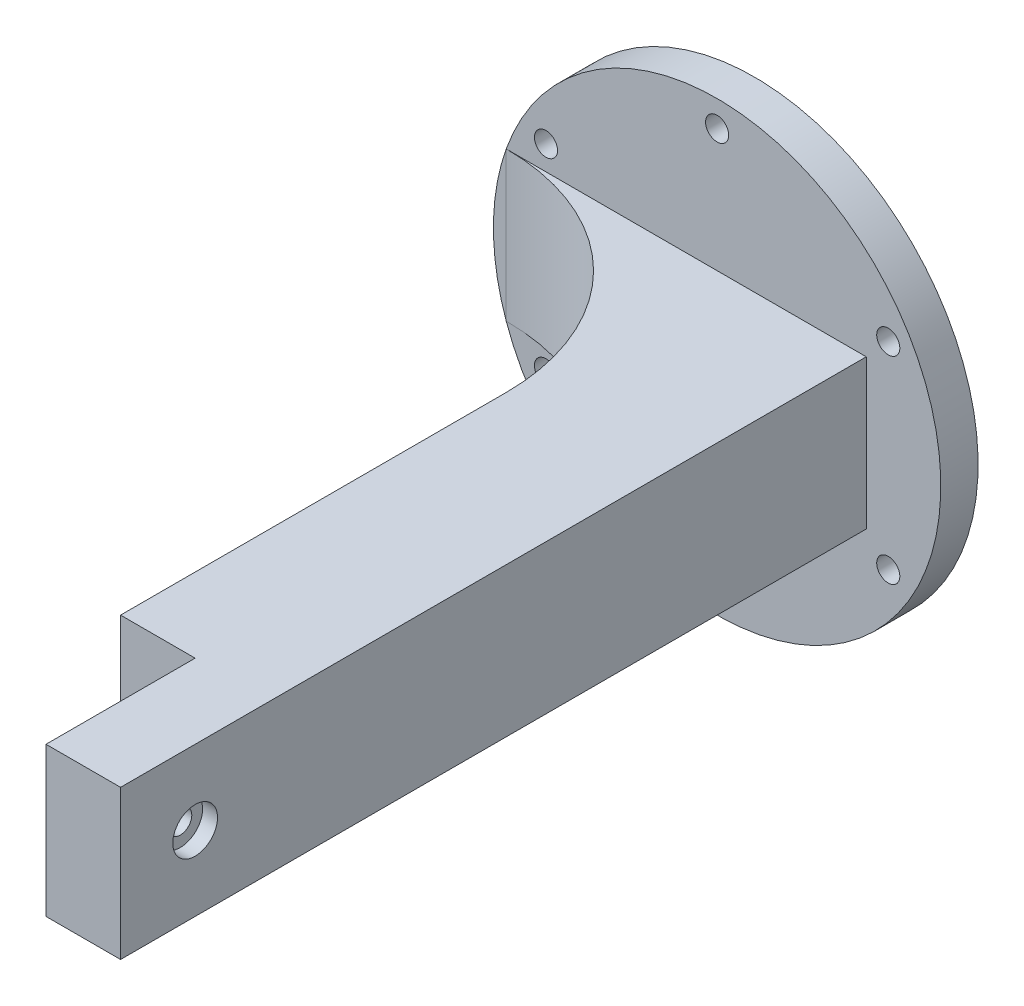
SolidWorks part; units mm, degrees
ref_plane "前视基准面" through (0, 0, 0) normal (0, 0, 1) x (1, 0, 0)
ref_plane "上视基准面" through (0, 0, 0) normal (0, 1, 0) x (1, 0, 0)
ref_plane "右视基准面" through (0, 0, 0) normal (1, 0, 0) x (0, 0, -1)
other "Configuration Table"
sketch "草图1" plane through (0, 0, 0) normal (0, 0, 1) x (1, 0, 0)
  line L1 (-16.3775, 3.1798) -> (3.6225, 3.1798)
  line L2 (-16.3775, 3.1798) -> (-16.3775, -16.8202)
  line L3 (-16.3775, -16.8202) -> (3.6225, -16.8202)
  line L4 (3.6225, 3.1798) -> (3.6225, -16.8202)
extrude "凸台-拉伸1" add sketch "草图1" along normal blind 140 contours L2 L1 L4 L3
sketch "草图2" plane through (0, 0, 0) normal (0, 0, -1) x (-1, 0, 0)
  line L1 (16.3775, 3.1798) -> (16.3775, -16.8202) construction
  circle A0 centre (16.3775, -6.8202) radius 30
  circle A4 centre (-6.5721, 6.4298) radius 1.55
  circle A5 centre (16.3775, 19.6798) radius 1.55
  circle A6 centre (39.3272, 6.4298) radius 1.55
  circle A7 centre (39.3272, -20.0702) radius 1.55
  circle A8 centre (16.3775, -33.3202) radius 1.55
  circle A9 centre (-6.5721, -20.0702) radius 1.55
extrude "凸台-拉伸2" add sketch "草图2" along normal blind 5 contours A4 | A9 | A8 | A7 | A0 | A6 | A5
sketch "草图3" plane through (0, 0, 0) normal (0, 0, 1) x (1, 0, 0)
  line L0 (-16.3775, 3.1798) -> (-44.6618, 3.1798)
  line L1 (-44.6618, 3.1798) -> (-44.6618, -16.8202)
  line L2 (-44.6618, -16.8202) -> (-16.3775, -16.8202)
  line L3 (-16.3775, 3.1798) -> (-16.3775, -16.8202)
  circle A0 centre (-16.3775, -6.8202) radius 30 construction
extrude "凸台-拉伸3" add sketch "草图3" along normal blind 28.2843 contours L3 L2 L1 L0
sketch "草图4" plane through (0, 3.1798, 0) normal (0, 1, 0) x (1, 0, 0)
  line L0 (-44.6618, -28.2843) -> (-44.6618, 0) construction
  line L1 (-44.6618, 0) -> (-44.6618, -28.2843)
  line L2 (-44.6618, -28.2843) -> (-16.3775, -28.2843)
  arc A0 (-16.3775, -28.2843) -> (-44.6618, 0) centre (-44.6618, -28.2843) ccw
extrude "切除-拉伸1" cut sketch "草图4" against normal blind 28.2843 contours L2 A0 L1
sketch "草图6" plane through (0, 3.1798, 0) normal (0, 1, 0) x (1, 0, 0)
  line L0 (3.6225, -140) -> (3.6225, -100)
  line L1 (3.6225, -140) -> (3.6225, 0) construction
  line L3 (-16.3775, -140) -> (-16.3775, -28.2843) construction
  line L4 (-16.3775, -100) -> (-16.3775, -140)
  line L5 (-16.3775, -140) -> (3.6225, -140)
  line L6 (-6.3775, -100) -> (-6.3775, -80)
  line L7 (-6.3775, -80) -> (-16.3775, -80)
  line L8 (-16.3775, -80) -> (-16.3775, -100)
  line L9 (-6.3775, -100) -> (3.6225, -100)
extrude "切除-拉伸2" cut sketch "草图6" against normal blind 28.2843 contours L9 L0 L5 L4 L8 L7 L6
sketch "草图7" plane through (-6.3775, 0, 0) normal (-1, 0, 0) x (0, 0, 1)
  line L0 (80, 3.1798) -> (100, -16.8202)
  line L1 (100, -16.8202) -> (100, 3.1798) construction
  circle A0 centre (90, -6.8202) radius 1.55
extrude "切除-拉伸3" cut sketch "草图7" against normal blind 28.2843 contours L0 A0 | L0 A0
sketch "草图8" plane through (3.6225, 0, 0) normal (1, 0, 0) x (0, 0, -1)
  circle A0 centre (-90, -6.8202) radius 3
extrude "切除-拉伸4" cut sketch "草图8" against normal blind 2 contours A0
sketch "草图9" plane through (0, 0, 80) normal (0, 0, 1) x (1, 0, 0)
  line L3 (-11.3775, -6.8202) -> (-11.3775, -10.8202)
  circle A0 centre (-11.3775, -10.8202) radius 2
extrude "切除-拉伸5" cut sketch "草图9" against normal blind 100
sketch "草图10" plane through (0, 0, -5) normal (0, 0, -1) x (-1, 0, 0)
  line L6 (11.3775, -10.8202) -> (12.7569, -12.2685)
  line L7 (11.3775, -10.8202) -> (10.2202, -9.189)
  line L8 (16.3775, -4.8202) -> (50.6831, -4.8202)
  line L9 (50.6831, -4.8202) -> (50.6831, -8.8202)
  line L10 (50.6831, -8.8202) -> (16.3775, -8.8202)
  line L11 (12.7569, -12.2685) -> (16.3775, -8.8202)
  line L12 (10.2202, -9.189) -> (16.3775, -4.8202)
extrude "切除-拉伸6" cut sketch "草图10" against normal blind 3 contours L11 L6 L7 L12 L8 L9 L10
sketch "草图11" plane through (0, 0, -5) normal (0, 0, -1) x (-1, 0, 0)
  line L0 (16.3775, 19.6798) -> (16.3775, -33.3202)
  line L1 (16.3775, -6.8202) -> (-3.6225, -6.8202)
  line L2 (-3.6225, -6.8202) -> (-3.6225, 3.1798)
  line L3 (-3.6225, -6.8202) -> (-3.6225, -16.8202)
  line L4 (-3.6225, 3.1798) -> (16.3775, 3.1798)
  line L5 (16.3775, 3.1798) -> (16.3775, -16.8202)
  line L6 (16.3775, -16.8202) -> (-3.6225, -16.8202)
  line M15 (16.3775, -8.8202) -> (12.7569, -12.2685)
  line M16 (12.7569, -12.2685) -> (12.7569, -12.2684)
  arc M17 (12.7569, -12.2684) -> (10.2202, -9.1891) centre (11.3775, -10.8202) cw
  line M18 (10.2202, -9.1891) -> (10.2202, -9.189)
  line M19 (10.2202, -9.189) -> (16.3775, -4.8202)
extrude "切除-拉伸7" cut sketch "草图11" against normal blind 3 contours L4 L2 L1 L0 M19 | L6 L0 L1 L3 M15 M16 M17 M18 M19 | L1 L0 M19 | L0 L1 M19 M18 M17 M16 M15
sketch "草图12" plane through (0, 0, -2) normal (0, 0, -1) x (-1, 0, 0)
  line L1 (-3.6225, -16.8202) -> (16.3775, -16.8202)
  line L2 (-3.6225, -16.8202) -> (-3.6225, 3.1798)
  line L3 (-3.6225, 3.1798) -> (16.3775, 3.1798)
  line L4 (16.3775, -16.8202) -> (16.3775, 3.1798)
  circle A0 centre (11.3775, -10.8202) radius 2
extrude "凸台-拉伸5" add sketch "草图12" along normal blind 3 contours L2 L1 L4 L3
sketch "草图13" plane through (0, 0, -5) normal (0, 0, -1) x (-1, 0, 0)
  line L2 (-3.6225, -6.8202) -> (-3.6225, -16.8202)
  line L3 (-3.6225, -6.8202) -> (-3.6225, 3.1798)
  line L4 (-3.6225, -16.8202) -> (16.3775, -16.8202)
  line L6 (0.6321, 4.9616) -> (0.6321, 5.0709)
  line L7 (-3.6225, 3.1798) -> (16.3775, 3.1798)
  line L8 (16.3775, 3.1798) -> (16.3775, -16.8202)
  line L9 (4.2562, -8.9415) -> (-0.34, -4.3453)
  line L10 (4.2562, -8.9415) -> (8.8524, -13.5377)
  line L11 (8.4989, -4.6989) -> (13.0951, -9.2951)
  line L12 (8.4989, -4.6989) -> (3.9027, -0.1027)
  line L13 (8.8524, -13.5377) -> (13.0951, -9.2951)
  line L14 (-0.34, -4.3453) -> (3.9027, -0.1027)
  circle M25 centre (11.3775, -10.8202) radius 2
extrude "切除-拉伸8" cut sketch "草图13" against normal blind 35 contours L14 L9 L10 L13 L11 L12 M25
sketch "草图14" plane through (0, 0, -5) normal (0, 0, -1) x (-1, 0, 0)
  line L0 (16.3775, -8.8202) -> (13.0951, -9.2951)
  line L4 (16.3775, -4.8202) -> (9.6006, -5.8006)
  line L5 (3.9027, -0.1027) -> (13.0951, -9.2951) construction
  line L6 (9.6006, -5.8006) -> (13.0951, -9.2951)
  line L7 (16.3775, -4.8202) -> (16.3775, -8.8202)
  line M8 (3.9027, -0.1027) -> (13.0951, -9.2951)
  line M11 (16.3775, -8.8202) -> (16.3775, -4.8202)
extrude "切除-拉伸9" cut sketch "草图14" against normal blind 3 contours L4 L0 M11 M8
sketch "草图15" plane through (0, 0, -5) normal (0, 0, -1) x (-1, 0, 0)
  line L0 (10.0628, -12.3273) -> (12.8847, -9.5054)
  arc A0 (10.0628, -12.3273) -> (12.8847, -9.5054) centre (11.3775, -10.8202) ccw
  arc A1 (10.0628, -12.3273) -> (12.8847, -9.5054) centre (11.3775, -10.8202) ccw construction
extrude "凸台-拉伸6" add sketch "草图15" against normal blind 35 contours L0 A0
